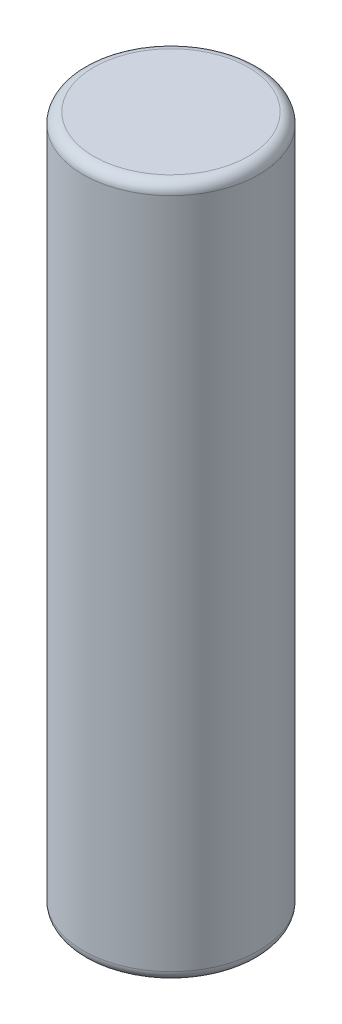
SolidWorks part; units mm, degrees
ref_plane "Alzado" through (0, 0, 0) normal (0, 0, 1) x (1, 0, 0)
ref_plane "Planta" through (0, 0, 0) normal (0, 1, 0) x (1, 0, 0)
ref_plane "Vista lateral" through (0, 0, 0) normal (1, 0, 0) x (0, 0, -1)
sketch "Croquis1" plane through (0, 0, 0) normal (0, 1, 0) x (1, 0, 0)
  circle A0 centre (0, 0) radius 8.3
  dimension "D1" = 16.6
extrude "Saliente-Extruir1" add sketch "Croquis1" along normal blind 65.5
fillet "Redondeo3" radius 1 2 edges at (0, 0, 8.3) (0, 65.5, 8.3)
